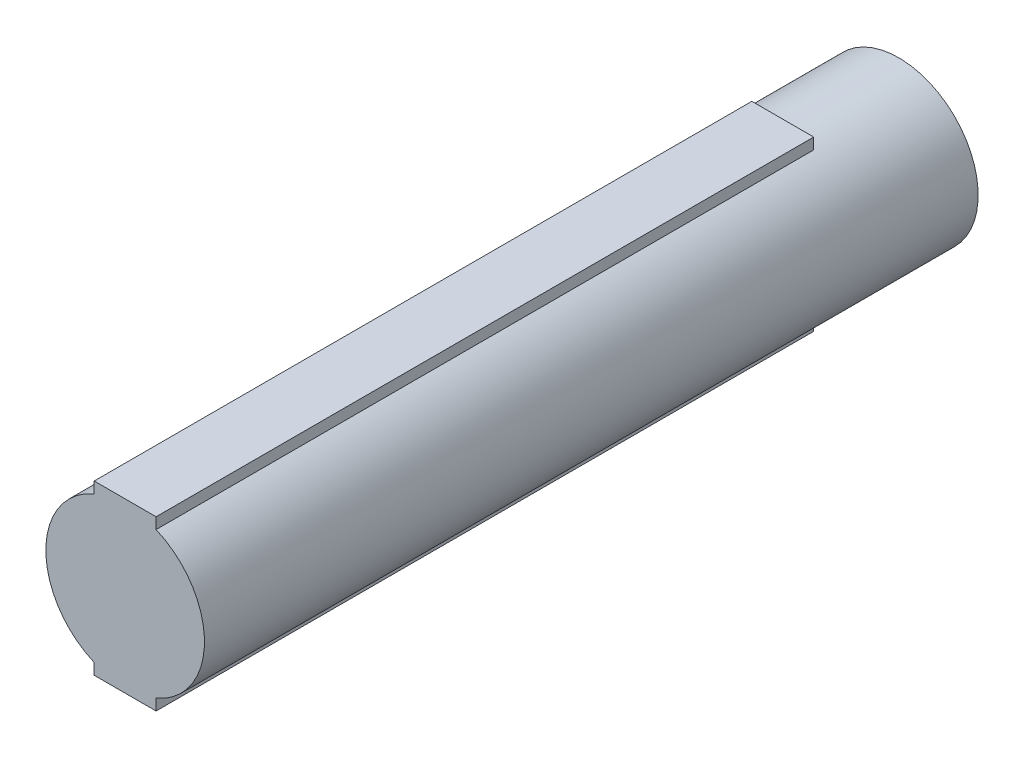
SolidWorks part; units mm, degrees
ref_plane "Front Plane" through (0, 0, 0) normal (0, 0, 1) x (1, 0, 0)
ref_plane "Top Plane" through (0, 0, 0) normal (0, 1, 0) x (1, 0, 0)
ref_plane "Right Plane" through (0, 0, 0) normal (1, 0, 0) x (0, 0, -1)
sketch "Sketch1" plane through (0, 0, 0) normal (0, 0, 1) x (1, 0, 0)
  line L0 (0, 0) -> (0, 1) construction
  line L1 (-1.12, 1) -> (1.12, 1)
  arc A0 (-1.5, 0) -> (1.5, 0) centre (0, 0) ccw
  arc A1 (-1.5, 0) -> (1.118, 1) centre (0, 0) ccw
  arc A2 (-1.5, 0) -> (-1.118, 1) centre (0, 0) cw
  circle A3 centre (0, 0) radius 2
  point P8 (0, 1)
  dimension "D1" = 1.5
  dimension "D4" = 4
  dimension "D2" = 1
  dimension "D3" = 2.24
extrude "Boss-Extrude1" add sketch "Sketch1" along normal blind 7
ref_plane "Plane1" through (0, 0, 3) normal (0, 0, 1) x (1, 0, 0)
sketch "Sketch2" plane through (0, 0, 3) normal (0, 0, 1) x (1, 0, 0)
  circle A0 centre (0, 0) radius 2
  circle A1 centre (0, 0) radius 2.05
  dimension "D1" = 4
  dimension "D2" = 4.1
sketch "Sketch3" plane through (0, 0, 7) normal (0, 0, 1) x (1, 0, 0)
  line L1 (-2.125, -0.75) -> (2.125, -0.75)
  line L2 (-2.125, -0.75) -> (-2.125, 0.75)
  line L3 (-2.125, 0.75) -> (2.125, 0.75)
  line L4 (2.125, -0.75) -> (2.125, 0.75)
  line L5 (-2.125, -0.75) -> (2.125, 0.75) construction
  line L6 (-2.125, 0.75) -> (2.125, -0.75) construction
  circle A1 centre (0, 0) radius 2
  circle A2 centre (0, 0) radius 2
  dimension "D2" = 4.25
  dimension "D3" = 1.5
  dimension "D1" = 0
extrude "Boss-Extrude3" add sketch "Sketch3" along normal blind 4 contours L3 L4 L1 L2 | A2
sketch "Sketch4" plane through (0, 0, 7) normal (0, 0, -1) x (-1, 0, 0)
  line L3 (-2.125, -0.75) -> (-1.854, -0.75)
  line L4 (-1.854, 0.75) -> (-2.125, 0.75)
  line L5 (-2.125, 0.75) -> (-2.125, -0.75)
  line L6 (-2.125, -0.75) -> (-1.854, -0.75)
  line L7 (-1.854, 0.75) -> (-2.125, 0.75)
  line L8 (-2.125, 0.75) -> (-2.125, -0.75)
  line L9 (2.125, 0.75) -> (1.854, 0.75)
  line L10 (1.854, -0.75) -> (2.125, -0.75)
  line L11 (2.125, -0.75) -> (2.125, 0.75)
  line L12 (2.125, 0.75) -> (1.854, 0.75)
  line L13 (1.854, -0.75) -> (2.125, -0.75)
  line L14 (2.125, -0.75) -> (2.125, 0.75)
  arc A1 (-1.854, 0.75) -> (-1.854, -0.75) centre (0, 0) ccw
  arc A2 (-1.854, 0.75) -> (-1.854, -0.75) centre (0, 0) ccw
  arc A3 (1.854, -0.75) -> (1.854, 0.75) centre (0, 0) ccw
  arc A4 (1.854, -0.75) -> (1.854, 0.75) centre (0, 0) ccw
  dimension "D1" = 0
  dimension "D2" = 0
extrude "Boss-Extrude4" add sketch "Sketch4" along normal blind 4
sketch "Sketch6" plane through (0, 0, 11) normal (0, 0, 1) x (1, 0, 0)
  line L0 (-0.75, -1.854) -> (-0.75, -2.125)
  line L1 (-0.75, -2.125) -> (0.75, -2.125)
  line L2 (0.75, -2.125) -> (0.75, -1.854)
  line L6 (-2.125, -0.75) -> (-1.854, -0.75)
  line L7 (1.854, -0.75) -> (2.125, -0.75)
  line L8 (2.125, -0.75) -> (2.125, 0.75)
  line L9 (2.125, 0.75) -> (1.854, 0.75)
  line L10 (-1.854, 0.75) -> (-2.125, 0.75)
  line L11 (-2.125, 0.75) -> (-2.125, -0.75)
  line L12 (-2.125, -0.75) -> (-1.854, -0.75)
  line L13 (1.854, -0.75) -> (2.125, -0.75)
  line L14 (2.125, -0.75) -> (2.125, 0.75)
  line L15 (2.125, 0.75) -> (1.854, 0.75)
  line L16 (-1.854, 0.75) -> (-2.125, 0.75)
  line L17 (-2.125, 0.75) -> (-2.125, -0.75)
  line L18 (0.75, 1.854) -> (0.75, 2.125)
  line L19 (0.75, 2.125) -> (-0.75, 2.125)
  line L20 (-0.75, 2.125) -> (-0.75, 1.854)
  line L21 (-1.854, 0.75) -> (-2.125, 0.75) [skipped]
  line L22 (-2.125, 0.75) -> (-2.125, -0.75) [skipped]
  line L23 (-2.125, -0.75) -> (-1.854, -0.75) [skipped]
  arc A0 (-1.854, 0.75) -> (-1.854, -0.75) centre (0, 0) ccw
  arc A1 (1.854, -0.75) -> (1.854, 0.75) centre (0, 0) ccw
  arc A2 (-1.854, -0.75) -> (1.854, -0.75) centre (0, 0) ccw
  arc A3 (1.854, 0.75) -> (-1.854, 0.75) centre (0, 0) ccw
  arc A6 (-0.75, -1.854) -> (0.75, -1.854) centre (0, 0) ccw
  arc A8 (0.75, 1.854) -> (-0.75, 1.854) centre (0, 0) ccw
  arc A9 (-1.854, 0.75) -> (-1.854, -0.75) centre (0, 0) ccw [skipped]
  point P25 (0, 0)
  dimension "D1" = 0
  dimension "D2" = 4
extrude "Boss-Extrude5" add sketch "Sketch6" against normal blind 8 contours L18 L19 L20 A8 | L0 L1 L2 A6
sketch "Sketch7" plane through (0, 0, 11) normal (0, 0, 1) x (1, 0, 0)
  line L12 (-2.125, -0.75) -> (-1.854, -0.75)
  line L13 (-0.75, 1.854) -> (-0.75, -2.125)
  line L14 (-0.75, -2.125) -> (0.75, -2.125)
  line L15 (0.75, -2.125) -> (0.75, 1.854)
  line L16 (1.854, -0.75) -> (2.125, -0.75)
  line L17 (2.125, -0.75) -> (2.125, 0.75)
  line L18 (2.125, 0.75) -> (1.854, 0.75)
  line L19 (0.75, 1.854) -> (0.75, 2.125)
  line L20 (0.75, 2.125) -> (-0.75, 2.125)
  line L21 (-0.75, 2.125) -> (-0.75, -1.854)
  line L22 (-1.854, 0.75) -> (-2.125, 0.75)
  line L23 (-2.125, 0.75) -> (-2.125, -0.75)
  line L24 (-2.125, -0.75) -> (-1.854, -0.75)
  line L28 (1.854, -0.75) -> (2.125, -0.75)
  line L29 (2.125, -0.75) -> (2.125, 0.75)
  line L30 (2.125, 0.75) -> (1.854, 0.75)
  line L34 (-1.854, 0.75) -> (-2.125, 0.75)
  line L35 (-2.125, 0.75) -> (-2.125, -0.75)
  arc A0 (-1.854, 0.75) -> (-1.854, -0.75) centre (0, 0) ccw
  arc A1 (1.854, -0.75) -> (1.854, 0.75) centre (0, 0) ccw
  arc A4 (-1.854, -0.75) -> (-0.75, 1.854) centre (0, 0) ccw
  arc A6 (1.854, 0.75) -> (0.75, 1.854) centre (0, 0) ccw
  arc A12 (0.75, 1.854) -> (1.854, -0.75) centre (0, 0) ccw
  arc A13 (-0.75, -1.854) -> (-1.854, 0.75) centre (0, 0) ccw
  dimension "D1" = 0
extrude "Cut-Extrude1" cut sketch "Sketch7" against normal blind 8
sketch "Sketch8" plane through (0, 0, 0) normal (0, 0, -1) x (-1, 0, 0)
  line L0 (-1.1832, 1.15) -> (1.1832, 1.15)
  line L1 (1.118, 1) -> (-1.118, 1) construction
  arc A0 (-1.118, 1) -> (1.118, 1) centre (0, 0) ccw construction
  arc A1 (-1.118, 1) -> (1.118, 1) centre (0, 0) ccw
  arc A2 (-1.1832, 1.15) -> (1.1832, 1.15) centre (0, 0) ccw
  arc M3 (1.118, 1) -> (-1.118, 1) centre (0, 0) cw
  line M4 (-1.118, 1) -> (1.118, 1)
  dimension "D1" = 0.15
  dimension "D2" = 0.15
extrude "Cut-Extrude2" cut sketch "Sketch8" against normal blind 7 contours L0 A2 M4 M3
extrude "Boss-Extrude6" add sketch "Sketch2" along normal blind 8 and the other way blind 3
sketch "Sketch10" plane through (0, 0, 3) normal (0, 0, -1) x (-1, 0, 0)
  line L3 (0.75, -2.125) -> (0.75, -1.9079)
  line L4 (-0.75, -1.9079) -> (-0.75, -2.125)
  line L5 (-0.75, -2.125) -> (0.75, -2.125)
  line L6 (0.75, -2.125) -> (0.75, -1.9079)
  line L7 (-0.75, -1.9079) -> (-0.75, -2.125)
  line L8 (-0.75, -2.125) -> (0.75, -2.125)
  line L9 (-0.75, 2.125) -> (-0.75, 1.9079)
  line L10 (0.75, 1.9079) -> (0.75, 2.125)
  line L11 (0.75, 2.125) -> (-0.75, 2.125)
  line L12 (-0.75, 2.125) -> (-0.75, 1.9079)
  line L13 (0.75, 1.9079) -> (0.75, 2.125)
  line L14 (0.75, 2.125) -> (-0.75, 2.125)
  line L15 (-0.8, 1.8875) -> (-0.8, 2.175)
  line L16 (-0.8, 2.175) -> (0.8, 2.175)
  line L17 (0.8, 2.175) -> (0.8, 1.8875)
  line L18 (0, 0) -> (0.4966, 0)
  line L19 (0.8, -2.175) -> (0.8, -1.8875)
  line L20 (-0.8, -1.8875) -> (-0.8, -2.175)
  line L21 (-0.8, -2.175) -> (0.8, -2.175)
  line L23 (-0.8, 2.175) -> (0.8, 2.175)
  line L24 (-0.8, 2.175) -> (-0.8, 1.8875)
  line L25 (-0.8, 1.8875) -> (0.8, 1.8875)
  line L26 (0.8, 2.175) -> (0.8, 1.8875)
  line L27 (-0.8, -2.175) -> (0.8, -2.175)
  line L28 (-0.8, -2.175) -> (-0.8, -1.8875)
  line L29 (-0.8, -1.8875) -> (0.8, -1.8875)
  line L30 (0.8, -2.175) -> (0.8, -1.8875)
  arc A1 (-0.75, -1.9079) -> (0.75, -1.9079) centre (0, 0) ccw
  arc A2 (-0.75, -1.9079) -> (0.75, -1.9079) centre (0, 0) ccw
  arc A3 (0.75, 1.9079) -> (-0.75, 1.9079) centre (0, 0) ccw
  arc A4 (0.75, 1.9079) -> (-0.75, 1.9079) centre (0, 0) ccw
  circle A5 centre (0, 0) radius 2.05 construction
  circle A6 centre (0, 0) radius 2.05
  point P17 (-0.8, 2.0312)
  point P20 (0.8, 2.0312)
  point P21 (0.8, -2.0312)
  line M22 (0.75, -2.125) -> (0.75, -1.9079)
  line M24 (-0.75, -1.9079) -> (-0.75, -2.125)
  line M25 (-0.75, -2.125) -> (0.75, -2.125)
  dimension "D3" = 0.05
  dimension "D4" = 0.05
  dimension "D1" = 0
  dimension "D2" = 0
extrude "Boss-Extrude7" add sketch "Sketch10" against normal blind 8 contours A6 L20 L21 L19 M22 M25 M24 | A6 L17 L16 L15 L12 L14 L13
sketch "Sketch11" plane through (0, 0, 0) normal (0, 0, -1) x (-1, 0, 0)
  line L0 (-1.2073, 1.05) -> (1.2073, 1.05)
  line L1 (-1.1832, 1.15) -> (1.1832, 1.15) construction
  arc A0 (-1.2073, 1.05) -> (1.2073, 1.05) centre (0, 0) ccw
  circle A1 centre (0, 0) radius 2.05
  circle A2 centre (0, 0) radius 2.05
  arc A3 (-1.1832, 1.15) -> (1.1832, 1.15) centre (0, 0) ccw construction
  dimension "D4" = 0.05
  dimension "D2" = 0.1
  dimension "D3" = 0.1
  dimension "D1" = 0
extrude "Boss-Extrude8" add sketch "Sketch11" along normal blind 9 and the other way blind 7
sketch "Sketch12" plane through (0, 0, 3) normal (0, 0, -1) x (-1, 0, 0)
  line L3 (-0.8, 2.175) -> (-0.8, 1.8875)
  line L4 (0.8, 1.8875) -> (0.8, 2.175)
  line L5 (0.8, 2.175) -> (-0.8, 2.175)
  line L6 (-0.8, 2.175) -> (-0.8, 1.8875)
  line L7 (0.8, 1.8875) -> (0.8, 2.175)
  line L8 (0.8, 2.175) -> (-0.8, 2.175)
  line L9 (0.8, -2.175) -> (0.8, -1.8875)
  line L10 (-0.8, -1.8875) -> (-0.8, -2.175)
  line L11 (-0.8, -2.175) -> (0.8, -2.175)
  line L12 (0.8, -2.175) -> (0.8, -1.8875)
  line L13 (-0.8, -1.8875) -> (-0.8, -2.175)
  line L14 (-0.8, -2.175) -> (0.8, -2.175)
  arc A1 (0.8, 1.8875) -> (-0.8, 1.8875) centre (0, 0) ccw
  arc A2 (0.8, 1.8875) -> (-0.8, 1.8875) centre (0, 0) ccw
  arc A3 (-0.8, -1.8875) -> (0.8, -1.8875) centre (0, 0) ccw
  arc A4 (-0.8, -1.8875) -> (0.8, -1.8875) centre (0, 0) ccw
  dimension "D1" = 0
  dimension "D2" = 0
extrude "Boss-Extrude9" add sketch "Sketch12" along normal blind 9
fillet "Fillet1" radius 0.1 2 edges at (-1.2073, 1.05, -1) (1.2073, 1.05, -1)
